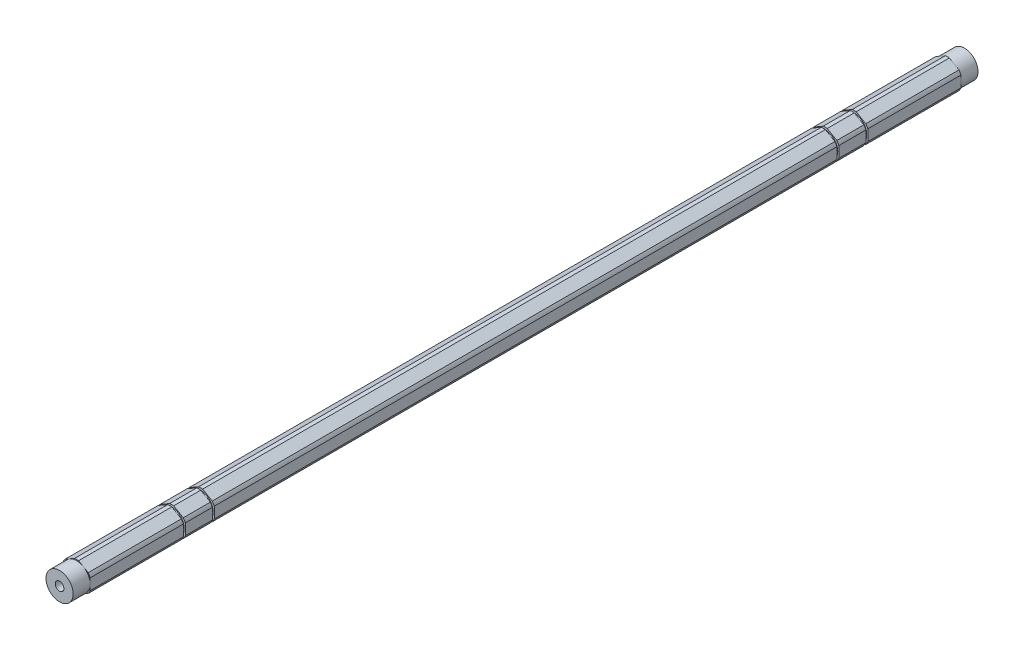
SolidWorks part; units mm, degrees
ref_plane "Front Plane" through (0, 0, 0) normal (0, 0, 1) x (1, 0, 0)
ref_plane "Top Plane" through (0, 0, 0) normal (0, 1, 0) x (1, 0, 0)
ref_plane "Right Plane" through (0, 0, 0) normal (1, 0, 0) x (0, 0, -1)
sketch "Sketch1" plane through (0, 0, 0) normal (0, 0, 1) x (1, 0, 0)
  line L1 (0, 7.3323) -> (-6.35, 3.6662)
  line L2 (-6.35, 3.6662) -> (-6.35, -3.6662)
  line L3 (-6.35, -3.6662) -> (0, -7.3323)
  line L4 (0, -7.3323) -> (6.35, -3.6662)
  line L5 (6.35, -3.6662) -> (6.35, 3.6662)
  line L6 (6.35, 3.6662) -> (0, 7.3323)
  circle A0 centre (0, 0) radius 6.35 construction
  circle A1 centre (0, 0) radius 6.858
  dimension "D1" = 12.7
  dimension "D2" = 13.716
extrude "Boss-Extrude1" add sketch "Sketch1" along normal mid plane 406.4 contours L5 A1 L6 L1 L2 L3 L4
sketch "Sketch6" plane through (0, 0, 203.2) normal (0, 0, 1) x (1, 0, 0)
  line L0 (5.4183, 4.2041) -> (0.9317, 6.7944) construction
  circle A0 centre (0, 0) radius 6.35
extrude "Boss-Extrude2" add sketch "Sketch6" along normal blind 7.9375
mirror "Mirror2" about plane through (0, 0, 0) normal (0, 0, 1) of "Boss-Extrude2"
hole_wizard "#10-32 Tapped Hole1" positions "3DSketch1" profile "Sketch2" tap size "#10-32" standard "ANSI Inch"
sketch3d "3DSketch1"
  line L0 (0, 0, 211.1375) -> (0, 0, 203.2) construction
  line L1 (0, 0, -211.1375) -> (0, 0, -203.2) construction
  point P11 (0, 0, 211.1375)
  point P15 (0, 0, -211.1375)
sketch "Sketch2" plane through (0, 0, 211.1375) normal (1, 0, 0) x (0, -1, 0)
  line L0 (0, 0) -> (0, 17.5608)
  line L1 (0, 17.5608) -> (2.0193, 16.3474)
  line L2 (2.0193, 16.3474) -> (2.0193, 0)
  line L5 (2.0193, 0) -> (0, 0)
  line L10 (0, 17.5608) -> (-2.0193, 16.3474) construction
  line L11 (0, -6.35) -> (0, 107.95) construction
  dimension "Tap Drill Dia." = 4.0386
  dimension "Tap Drill Depth" = 16.3474
  dimension "Drill Angle" = 118
cosmetic thread "Hole Thread1" parameters "D1"=13.97, "D2"=4.826
cosmetic thread "Hole Thread2" parameters "D1"=13.97, "D2"=4.826
sketch "Sketch5" plane through (0, 0, 0) normal (1, 0, 0) x (0, 0, -1)
  line L0 (203.2, 6.858) -> (-203.2, 6.858) construction
  line L1 (-159.7076, 6.858) -> (-158.8186, 6.858)
  line L2 (-159.7076, 6.858) -> (-159.7076, 5.8547)
  line L3 (-159.7076, 5.8547) -> (-158.8186, 5.8547)
  line L4 (-158.8186, 6.858) -> (-158.8186, 5.8547)
  line L5 (-165.0472, 0) -> (-158.8423, 0) construction
  line L6 (-146.1821, 6.858) -> (-145.2931, 6.858)
  line L7 (-146.1821, 6.858) -> (-146.1821, 5.8547)
  line L8 (-146.1821, 5.8547) -> (-145.2931, 5.8547)
  line L9 (-145.2931, 6.858) -> (-145.2931, 5.8547)
  dimension "D1" = 5.8547
  dimension "D2" = 0.889
  dimension "D3" = 44.3814
  dimension "D4" = 12.6365
revolve "Cut-Revolve1" cut sketch "Sketch5" angle 360 about L5
mirror "Mirror1" about plane through (0, 0, 0) normal (0, 0, 1) of "Cut-Revolve1"
